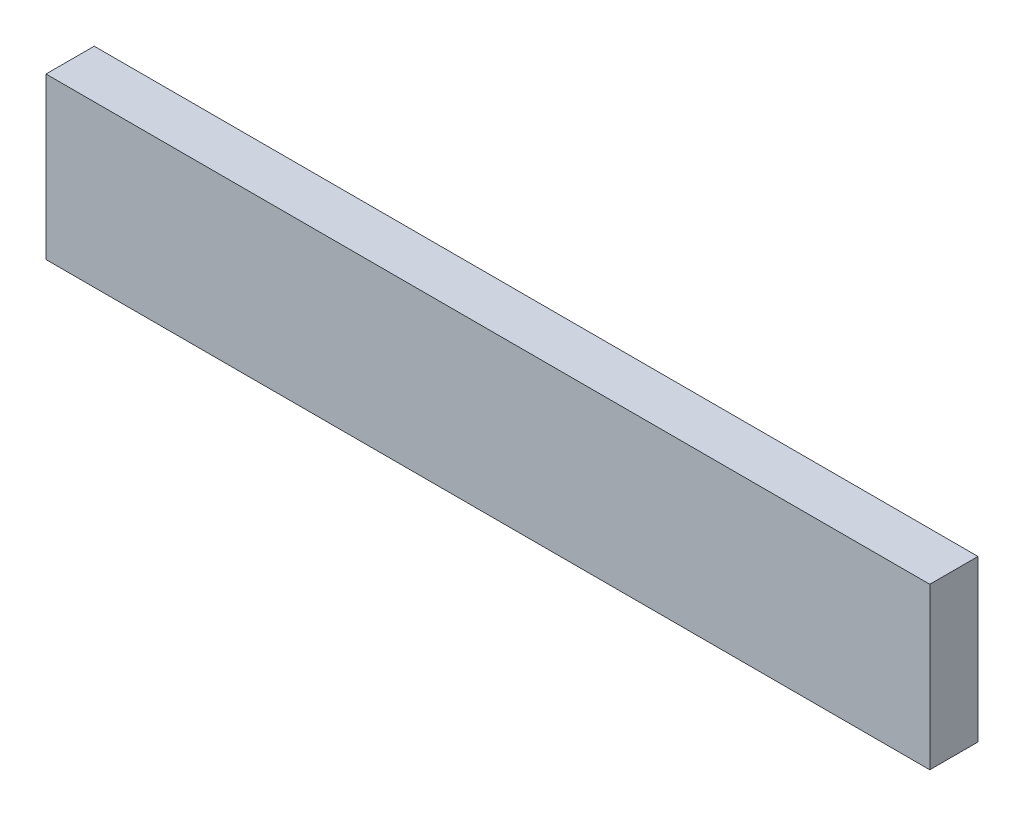
SolidWorks part; units mm, degrees
ref_plane "Front Plane" through (0, 0, 0) normal (0, 0, 1) x (1, 0, 0)
ref_plane "Top Plane" through (0, 0, 0) normal (0, 1, 0) x (1, 0, 0)
ref_plane "Right Plane" through (0, 0, 0) normal (1, 0, 0) x (0, 0, -1)
sketch "Sketch1" plane through (0, 0, 0) normal (0, 0, 1) x (1, 0, 0)
  line L1 (0, 0) -> (55, 0)
  line L2 (0, 0) -> (0, 10)
  line L3 (0, 10) -> (55, 10)
  line L4 (55, 0) -> (55, 10)
  dimension "D1" = 55
  dimension "D2" = 10
extrude "Boss-Extrude1" add sketch "Sketch1" along normal blind 3
